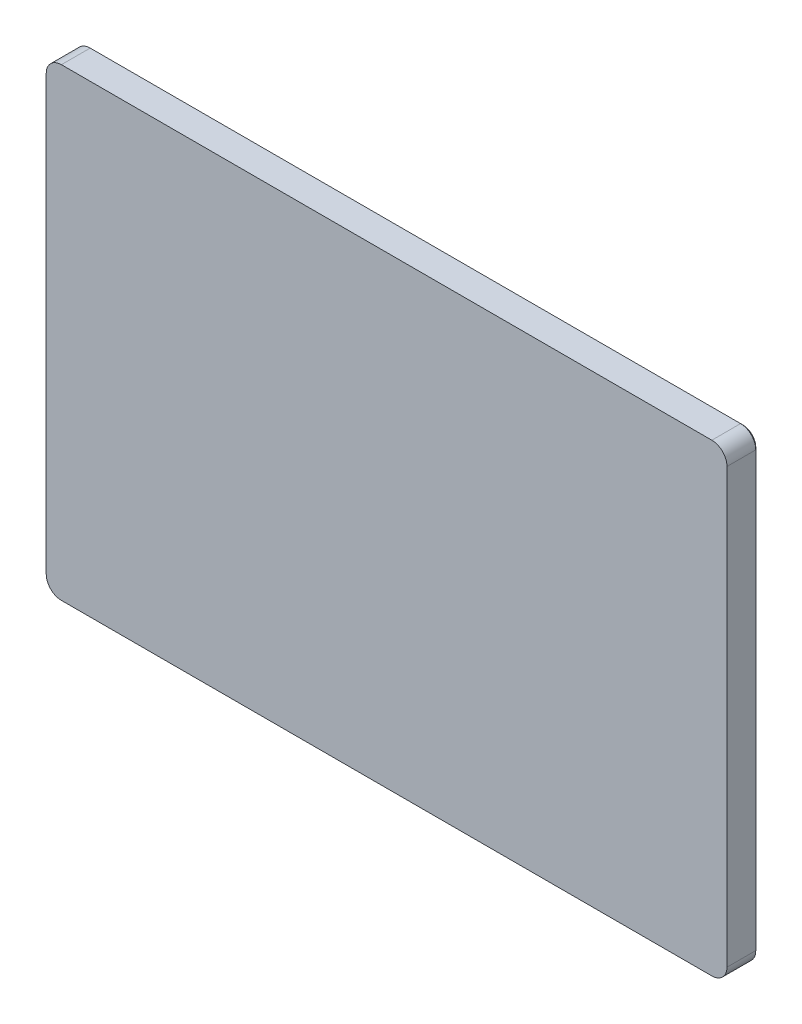
SolidWorks part; units mm, degrees
ref_plane "Front" through (0, 0, 0) normal (0, 0, 1) x (1, 0, 0)
ref_plane "Top" through (0, 0, 0) normal (0, 1, 0) x (1, 0, 0)
ref_plane "Right" through (0, 0, 0) normal (1, 0, 0) x (0, 0, -1)
sketch "Sketch1" plane through (0, 0, 0) normal (0, 0, 1) x (1, 0, 0)
  line L0 (86.5, 55) -> (86.5, -55) construction
  line L5 (82.5, -59) -> (-82.5, -59) construction
  line L6 (-86.5, -55) -> (-86.5, 55) construction
  line L7 (-82.5, 59) -> (82.5, 59) construction
  line L8 (86.5, 55) -> (86.5, -55) construction
  line L9 (82.5, -59) -> (-82.5, -59) construction
  line L10 (-86.5, -55) -> (-86.5, 55) construction
  line L11 (-82.5, 59) -> (82.5, 59) construction
  line L12 (-82.5, 58.85) -> (82.5, 58.85)
  line L13 (86.35, 55) -> (86.35, -55)
  line L14 (82.5, -58.85) -> (-82.5, -58.85)
  line L15 (-86.35, -55) -> (-86.35, 55)
  arc A0 (86.5, 55) -> (82.5, 59) centre (82.5, 55) ccw construction
  arc A1 (82.5, -59) -> (86.5, -55) centre (82.5, -55) ccw construction
  arc A2 (-86.5, -55) -> (-82.5, -59) centre (-82.5, -55) ccw construction
  arc A3 (-82.5, 59) -> (-86.5, 55) centre (-82.5, 55) ccw construction
  arc A4 (86.5, 55) -> (82.5, 59) centre (82.5, 55) ccw construction
  arc A5 (82.5, -59) -> (86.5, -55) centre (82.5, -55) ccw construction
  arc A6 (-86.5, -55) -> (-82.5, -59) centre (-82.5, -55) ccw construction
  arc A7 (-82.5, 59) -> (-86.5, 55) centre (-82.5, 55) ccw construction
  arc A8 (86.35, 55) -> (82.5, 58.85) centre (82.5, 55) ccw
  arc A9 (82.5, -58.85) -> (86.35, -55) centre (82.5, -55) ccw
  arc A10 (-86.35, -55) -> (-82.5, -58.85) centre (-82.5, -55) ccw
  arc A11 (-82.5, 58.85) -> (-86.35, 55) centre (-82.5, 55) ccw
  dimension "D1" = 0.15
extrude "Boss-Extrude1" add sketch "Sketch1" along normal up to surface (7.9 mm away)
chamfer "Chamfer1" distance 0.6 angle 45 8 edges at (86.35, 0, 0) (85.2224, 57.7224, 0) (85.2224, -57.7224, 0) (0, 58.85, 0) (0, -58.85, 0) (-85.2224, 57.7224, 0) (-85.2224, -57.7224, 0) (-86.35, 0, 0)
